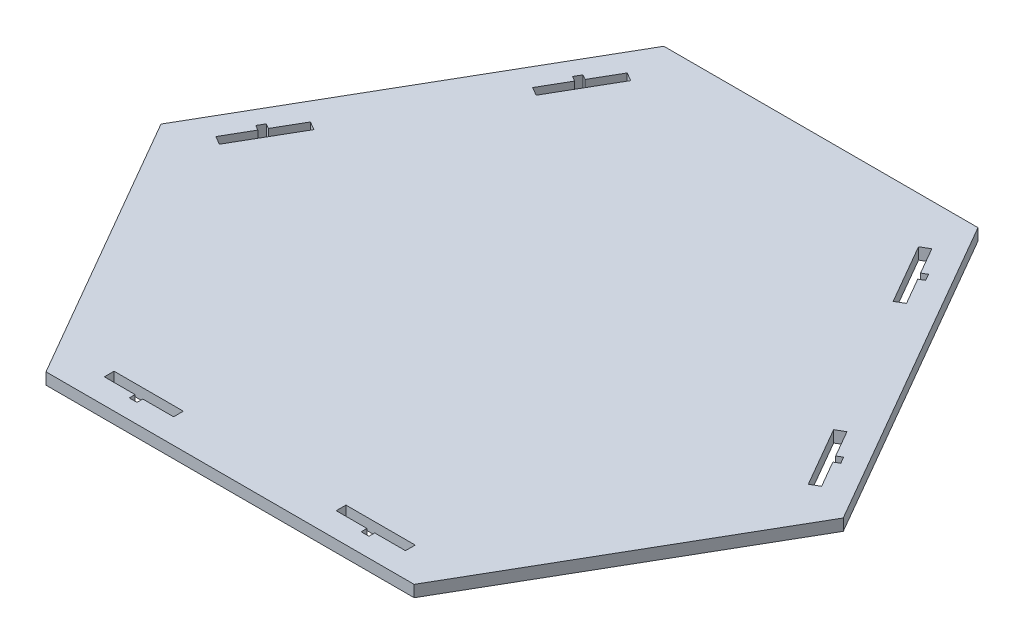
SolidWorks part; units mm, degrees
ref_plane "Front Plane" through (0, 0, 0) normal (0, 0, 1) x (1, 0, 0)
ref_plane "Top Plane" through (0, 0, 0) normal (0, 1, 0) x (1, 0, 0)
ref_plane "Right Plane" through (0, 0, 0) normal (1, 0, 0) x (0, 0, -1)
sketch "Sketch1" plane through (0, 0, 0) normal (0, 1, 0) x (1, 0, 0)
  line L0 (-40.64, 78.4561) -> (40.64, 78.4561)
  line L1 (40.64, 78.4561) -> (88.265, -4.0328)
  line L2 (88.265, -4.0328) -> (47.625, -74.4233)
  line L3 (47.625, -74.4233) -> (-47.625, -74.4233)
  line L4 (-47.625, -74.4233) -> (-88.265, -4.0328)
  line L5 (-88.265, -4.0328) -> (-40.64, 78.4561)
  line L6 (-64.4525, 37.2117) -> (64.4525, 37.2117) construction
  line L7 (64.4525, 37.2117) -> (0, -74.4233) construction
  line L8 (0, -74.4233) -> (-64.4525, 37.2117) construction
  line L9 (-67.945, -39.2281) -> (67.945, -39.2281) construction
  line L10 (-67.945, -39.2281) -> (0, 78.4561) construction
  line L11 (0, 78.4561) -> (67.945, -39.2281) construction
  circle A0 centre (0, 0) radius 78.4561 construction
  circle A1 centre (0, 0) radius 74.4233 construction
  point P9 (-67.945, -39.2281)
  point P10 (67.945, -39.2281)
  point P11 (67.945, -39.2281)
  point P14 (0, 78.4561)
  dimension "D1" = 60
  dimension "D2" = 60
  dimension "D3" = 81.28
  dimension "D4" = 95.25
extrude "Boss-Extrude1" add sketch "Sketch1" along normal blind 3
sketch "Sketch2" plane through (0, 3, 0) normal (0, 1, 0) x (1, 0, 0)
  line L0 (29, -68) -> (29, -69.5)
  line L1 (21.04, -65.48) -> (38.96, -65.48)
  line L2 (21.04, -65.48) -> (21.04, -68)
  line L3 (21.04, -68) -> (29, -68)
  line L4 (38.96, -65.48) -> (38.96, -68)
  line L5 (29, -69.5) -> (31, -69.5)
  line L6 (31, -69.5) -> (31, -68)
  line L7 (31, -68) -> (38.96, -68)
  line L8 (30, -69.5) -> (30, -65.48) construction
  point P4 (30, -65.48)
  dimension "D1" = 17.92
  dimension "D2" = 2.52
  dimension "D3" = 30
  dimension "D4" = 68
  dimension "D5" = 2
  dimension "D6" = 1.5
sketch "Sketch3" plane through (0, 0, 0) normal (1, 0, 0) x (0, 0, -1)
  line L0 (0, 0) -> (0, 63.1087) construction
extrude "Cut-Extrude1" cut sketch "Sketch2" against normal through all
mirror "Mirror1" about plane through (0, 0, 0) normal (1, 0, 0) of "Cut-Extrude1"
pattern_circular "CirPattern1" count 3 over 360 about axis through (0, 0, 0) along (0, 1, 0) of "Mirror1", "Cut-Extrude1"
